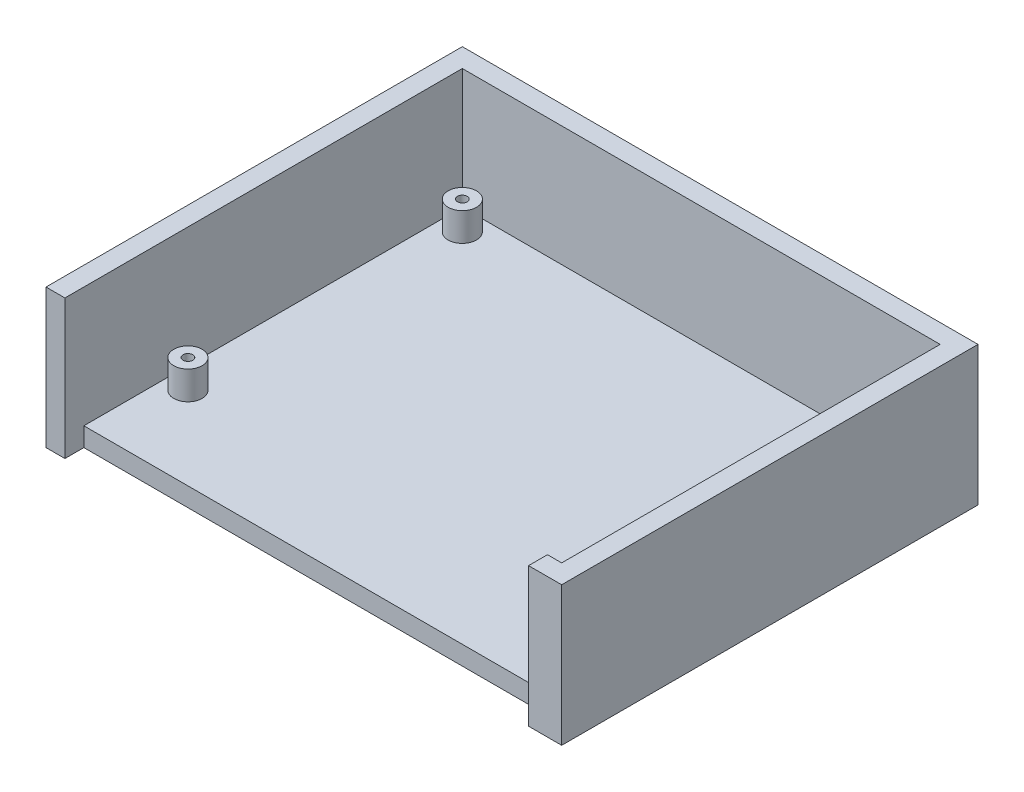
SolidWorks part; units mm, degrees
ref_plane "Front Plane" through (0, 0, 0) normal (0, 0, 1) x (1, 0, 0)
ref_plane "Top Plane" through (0, 0, 0) normal (0, 1, 0) x (1, 0, 0)
ref_plane "Right Plane" through (0, 0, 0) normal (1, 0, 0) x (0, 0, -1)
sketch "Sketch2" plane through (0, 0, 0) normal (0, 1, 0) x (1, 0, 0)
  line L1 (50.5, -40) -> (-50.5, -40)
  line L2 (50.5, -40) -> (50.5, 40)
  line L3 (50.5, 40) -> (-50.5, 40)
  line L4 (-50.5, -40) -> (-50.5, 40)
  line L5 (50.5, -40) -> (-50.5, 40) construction
  line L6 (50.5, 40) -> (-50.5, -40) construction
  point P0 (0, 0)
  dimension "D1" = 101
  dimension "D2" = 80
extrude "Boss-Extrude1" add sketch "Sketch2" along normal blind 4
sketch "Sketch3" plane through (0, 0, 0) normal (0, -1, 0) x (1, 0, 0)
  line L1 (50.5, -40) -> (-50.5, -40)
  line L2 (50.5, -40) -> (50.5, 40)
  line L4 (-50.5, -40) -> (-50.5, 40)
  line L5 (50.5, -40) -> (-50.5, 40) construction
  line L6 (50.5, 40) -> (-50.5, -40) construction
  line L8 (54.5, 44) -> (54.5, -44)
  line L9 (54.5, -44) -> (-54.5, -44)
  line L10 (-54.5, 44) -> (-54.5, -44)
  line L11 (54.5, 44) -> (-54.5, -44) construction
  line L12 (54.5, -44) -> (-54.5, 44) construction
  line L13 (-50.5, 40) -> (50.5, 40) construction
  line L14 (-50.5, 40) -> (-50.5, 44)
  line L15 (-50.5, 44) -> (-54.5, 44)
  line L16 (54.5, 44) -> (47.5, 44)
  line L17 (47.5, 44) -> (47.5, 40)
  line L18 (47.5, 40) -> (50.5, 40)
  line L19 (-50.5, 0) -> (-54.5, 0) construction
  line L20 (0, -40) -> (0, -44) construction
  point P0 (0, 0)
  point P7 (0, 0)
  dimension "D1" = 4
  dimension "D3" = 7
extrude "Boss-Extrude2" add sketch "Sketch3" against normal offset from surface (29.4 mm away) 25.4 up to face at (0, 4, 0) offset beyond the face yes
sketch "Sketch9" plane through (0, 4, 0) normal (0, 1, 0) x (1, 0, 0)
  circle A0 centre (-46, -22.5) radius 3
  circle A1 centre (-46, 35.5) radius 3
  circle A2 centre (40, 35.5) radius 3
  circle A3 centre (40, -22.5) radius 3
  point P8 (0, 0)
  point P9 (0, 0)
  point P10 (0, 0)
  point P11 (0, 0)
  dimension "D1" = 6
extrude "Boss-Extrude3" add sketch "Sketch9" along normal blind 6
hole_wizard "M2.5x0.45 Tapped Hole1" positions "Sketch10" profile "Sketch11" tap size "M2.5x0.45" standard "ANSI Metric" end condition through all
sketch "Sketch10" plane through (0, 10, 0) normal (0, 1, 0) x (1, 0, 0)
  circle A0 centre (40, -22.5) radius 3 construction
  circle A1 centre (-46, -22.5) radius 3 construction
  circle A4 centre (-46, 35.5) radius 3 construction
  circle A5 centre (40, 35.5) radius 3 construction
  point P0 (-46, -22.5)
  point P2 (-46, 35.5)
  point P4 (40, 35.5)
  point P6 (40, -22.5)
  point P30 (0, 0)
  point P33 (0, 0)
sketch "Sketch11" plane through (-46, 10, 22.5) normal (1, 0, 0) x (0, 0, 1)
  line L0 (0, 0) -> (0, 10)
  line L1 (0, 10) -> (1.025, 10)
  line L2 (1.025, 10) -> (1.025, 0)
  line L5 (1.025, 0) -> (0, 0)
  line L11 (0, -6.35) -> (0, 107.95) construction
  dimension "Thru Tap Drill Dia." = 2.05
  dimension "Thru Tap Drill Depth" = 10
cosmetic thread "Hole Thread5" parameters "D2"=2.5
cosmetic thread "Hole Thread6" parameters "D2"=2.5
cosmetic thread "Hole Thread7" parameters "D2"=2.5
cosmetic thread "Hole Thread8" parameters "D2"=2.5
